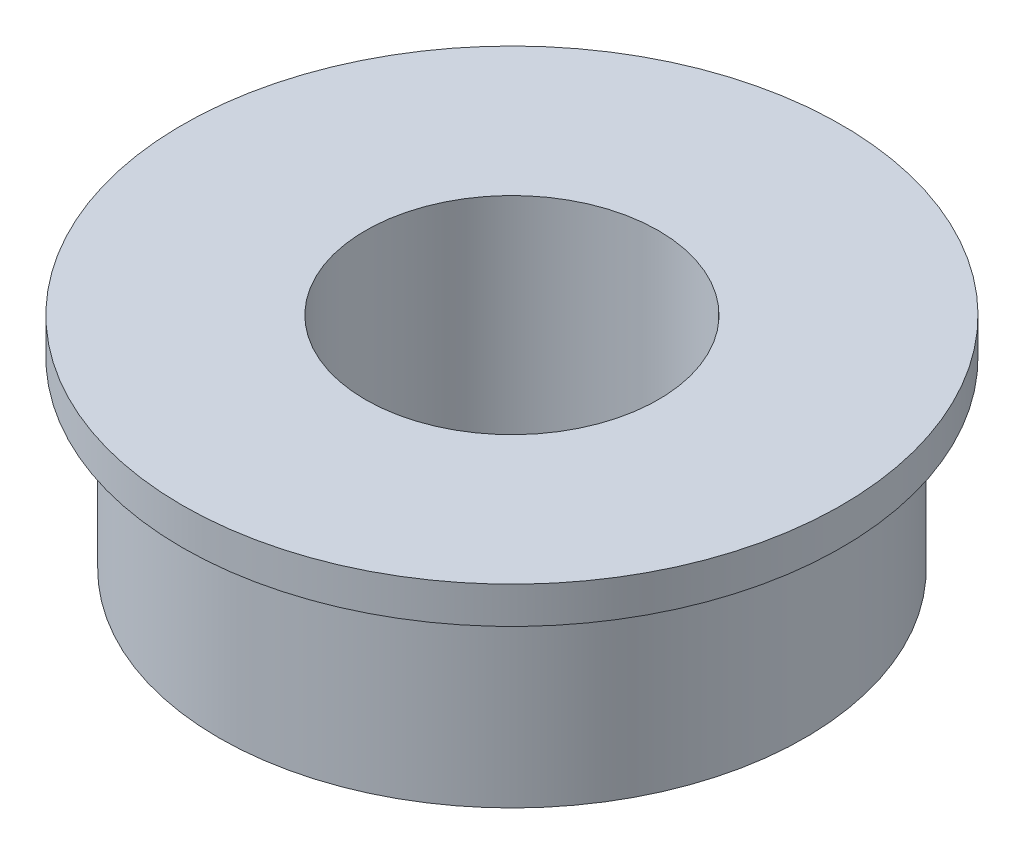
SolidWorks part; units mm, degrees
ref_plane "前视基准面" through (0, 0, 0) normal (0, 0, 1) x (1, 0, 0)
ref_plane "上视基准面" through (0, 0, 0) normal (0, 1, 0) x (1, 0, 0)
ref_plane "右视基准面" through (0, 0, 0) normal (1, 0, 0) x (0, 0, -1)
sketch "草图1" plane through (0, 0, 0) normal (0, 1, 0) x (1, 0, 0)
  circle A0 centre (0, 0) radius 2
  circle A1 centre (0, 0) radius 4
extrude "凸台-拉伸1" add sketch "草图1" along normal blind 3
sketch "草图2" plane through (0, 3, 0) normal (0, 1, 0) x (1, 0, 0)
  circle A0 centre (0, 0) radius 2
  circle A1 centre (0, 0) radius 4.5
  dimension "D1" = 9
extrude "凸台-拉伸2" add sketch "草图2" against normal blind 0.5
